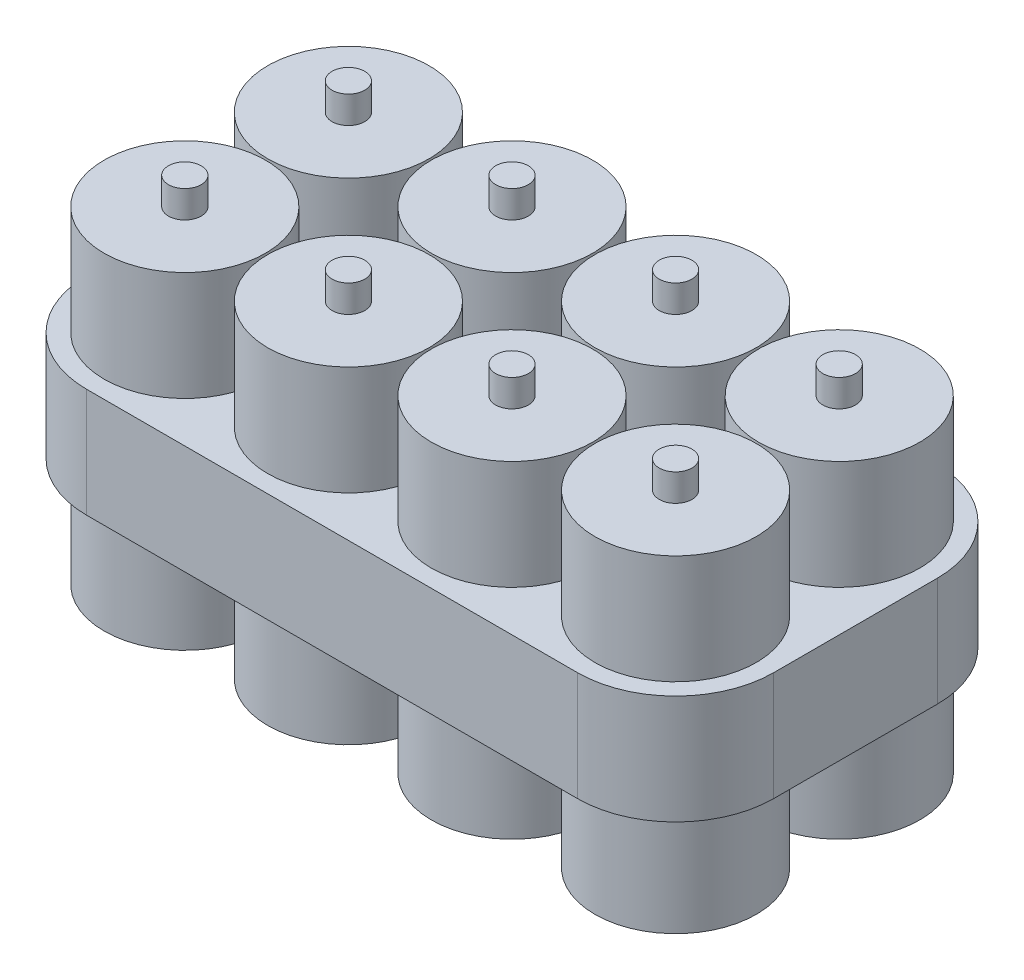
SolidWorks part; units mm, degrees
ref_plane "前视基准面" through (0, 0, 0) normal (0, 0, 1) x (1, 0, 0)
ref_plane "上视基准面" through (0, 0, 0) normal (0, 1, 0) x (1, 0, 0)
ref_plane "右视基准面" through (0, 0, 0) normal (1, 0, 0) x (0, 0, -1)
ref_plane "基准面1" through (0, 20, 0) normal (0, 1, 0) x (1, 0, 0)
sketch "草图3" plane through (0, 20, 0) normal (0, 1, 0) x (1, 0, 0)
  line L6 (0, 48) -> (90, 48)
  line L7 (-18, 30) -> (-18, 0)
  line L8 (108, 30) -> (108, 0)
  line L10 (0, -18) -> (90, -18)
  line L11 (0, 45) -> (0, 44.9)
  line L13 (90, 44.9) -> (90, 45)
  arc A5 (0, 48) -> (-18, 30) centre (0, 30) ccw
  arc A6 (90, 48) -> (108, 30) centre (90, 30) cw
  arc A7 (108, 0) -> (90, -18) centre (90, 0) cw
  arc A8 (0, -18) -> (-18, 0) centre (0, 0) cw
extrude "凸台-拉伸8" add sketch "草图3" along normal blind 20
sketch "草图1" plane through (0, 0, 0) normal (0, 1, 0) x (1, 0, 0)
  circle A0 centre (0, 0) radius 14.8
  circle A1 centre (30, 0) radius 14.8
  circle A2 centre (60, 0) radius 14.8
  circle A3 centre (90, 0) radius 14.8
  circle A4 centre (0, 30) radius 14.8
  circle A5 centre (30, 30) radius 14.8
  circle A6 centre (60, 30) radius 14.8
  circle A7 centre (90, 30) radius 14.8
  dimension "D1" = 4
extrude "凸台-拉伸1" add sketch "草图1" along normal blind 60 contours A4 | A5 | A6 | A7 | A3 | A2 | A1 | A0
sketch "草图2" plane through (0, 60, 0) normal (0, 1, 0) x (1, 0, 0)
  circle A0 centre (0, 30) radius 3
  circle A1 centre (30, 30) radius 3
  circle A2 centre (60, 30) radius 3
  circle A3 centre (90, 30) radius 3
  circle A4 centre (30, 0) radius 3
  circle A5 centre (60, 0) radius 3
  circle A6 centre (90, 0) radius 3
  circle A7 centre (0, 0) radius 3
extrude "凸台-拉伸2" add sketch "草图2" along normal blind 5
